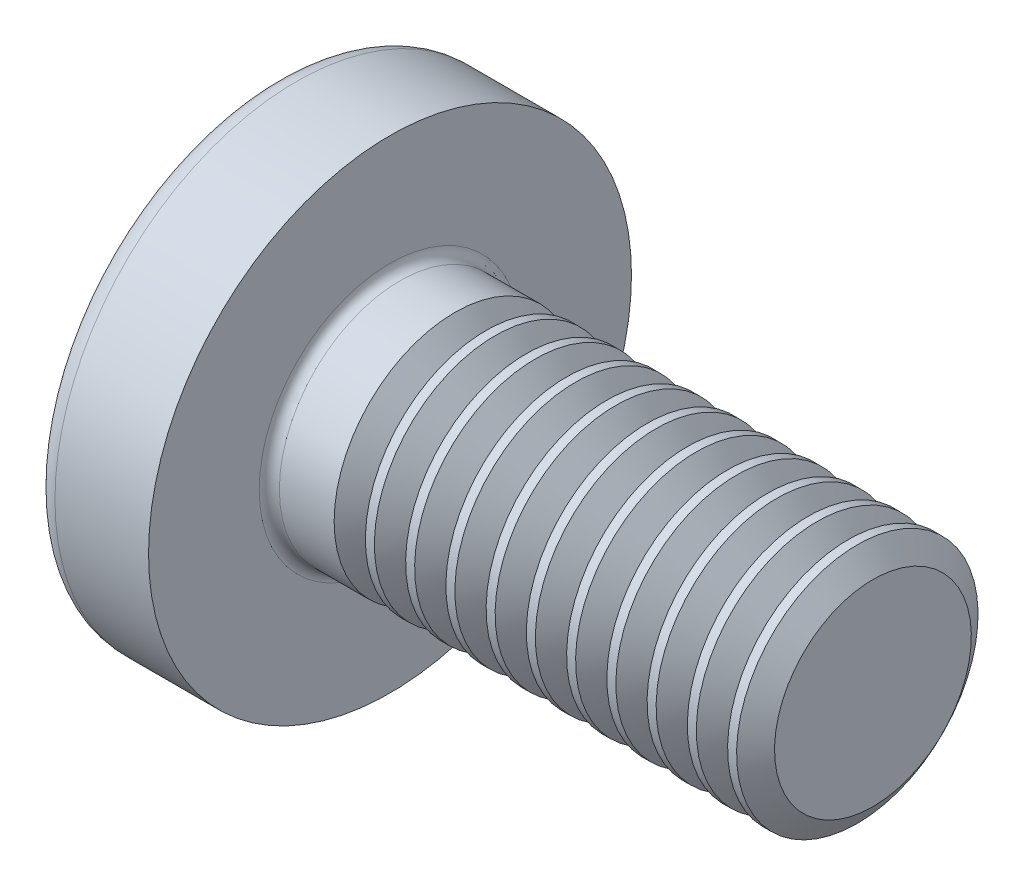
SolidWorks part; units mm, degrees
ref_plane "Plane1" through (0, 0, 0) normal (0, 0, 1) x (1, 0, 0)
ref_plane "Plane2" through (0, 0, 0) normal (0, 1, 0) x (1, 0, 0)
ref_plane "Plane3" through (0, 0, 0) normal (1, 0, 0) x (0, 0, -1)
sketch "BodySke" plane through (0, 0, 0) normal (0, 0, 1) x (1, 0, 0)
  line L0 (4.6, 3) -> (4.6, 6)
  line L1 (5.1, 6.35) -> (5.1, -3.175) construction
  line L2 (-25.4, 0) -> (127, 0) construction
  line L3 (16.6, 0) -> (0, 0)
  line L4 (4.6, 3) -> (16.6, 3)
  line L5 (16.6, 3) -> (16.6, 0)
  line L6 (2.2747, 6) -> (4.6, 6)
  line L8 (4.6, 6.35) -> (4.6, -3.175) construction
  arc A0 (1.8337, 5.7717) -> (0, 0) centre (10, 0) ccw
  arc A2 (1.8337, 5.7717) -> (2.2747, 6) centre (2.2747, 5.46) cw
  dimension "Head_fillet_rad" = 0.54
  dimension "Head_crown_rad" = 10
  dimension "Head_ht" = 4.6
  dimension "Diameter" = 6
  dimension "Length" = 12
  dimension "Head_dia" = 12
  dimension "Advance" = 1
  dimension "Thread_nom" = 12
revolve "Base-Revolve" add sketch "BodySke"
cosmetic thread "ThreadCosmetic" [suppressed]
fillet "Fillet1" radius 0.25 1 edges at (4.6, 0, 3)
sketch "Sketch3" plane through (0, 0, 0) normal (1, 0, 0) x (0, 0, -1)
  line L0 (0.71, -3.35) -> (-0.71, -3.35)
  line L1 (0.71, -3.35) -> (0.71, 3.35)
  line L2 (-0.71, 3.35) -> (0.71, 3.35)
  line L3 (-0.71, 3.35) -> (-0.71, -3.35)
  dimension "D1" = 3.35
  dimension "Cross_dia" = 6.7
  dimension "D2" = 0.71
  dimension "Cross_width" = 1.42
ref_plane "Plane4" through (3.46, 0, 0) normal (1, 0, 0) x (0, 0, -1)
sketch "Sketch4" plane through (3.46, 0, 0) normal (1, 0, 0) x (0, 0, -1)
  line L0 (0.71, -1.6249) -> (-0.71, -1.6249)
  line L1 (0.71, -1.6249) -> (0.71, 1.6249)
  line L2 (-0.71, 1.6249) -> (0.71, 1.6249)
  line L3 (-0.71, 1.6249) -> (-0.71, -1.6249)
  dimension "D1" = 1.42
  dimension "D2" = 3.2498
  dimension "D3" = 0.71
  dimension "D4" = 1.6249
loft "Recess" cut profiles "Sketch3", "Sketch4"
pattern_circular "RecPat" count 2 every 90 about axis through (0, 0, 0) along (1, 0, 0) of "Recess"
sketch "RecCorSke" plane through (0, 0, 0) normal (0, 0, 1) x (1, 0, 0)
  line L0 (-3.175, 0) -> (15.875, 0) construction
  line L1 (-25.4, 0) -> (127, 0) construction
  line L2 (0, 0) -> (0, 1.5224)
  line L3 (0, 1.5224) -> (3.46, 1.2805)
  line L4 (3.46, 1.2805) -> (3.8761, 0)
  line L5 (3.8761, 0) -> (0, 0)
  dimension "Diameter" = 2.561
  dimension "Depth" = 3.46
  dimension "Draft_angle" = 4
  dimension "Bottom_angle" = 18
revolve "RecessCore" cut sketch "RecCorSke" angle 360 about L0
sketch "ThdSchSke" plane through (0, 0, 0) normal (0, 0, 1) x (1, 0, 0)
  line L0 (6.6, -2.4455) -> (6.2117, -3)
  line L1 (6.6, -2.4455) -> (6.9883, -3)
  line L2 (6.9883, -3) -> (6.9883, -3.75)
  line L3 (-3.175, 0) -> (5.1513, 0) construction
  line L5 (6.9883, -3.75) -> (6.2117, -3.75)
  line L6 (6.2117, -3.75) -> (6.2117, -3)
  dimension "Thread_minor" = 4.891
  dimension "Diameter" = 6
  dimension "Start" = 6.6
  dimension "SideAngle" = 55
  dimension "VeeAngle" = 70
  dimension "Overcut" = 7.5
revolve "ThreadSchematic" cut sketch "ThdSchSke" angle 360 about L3
pattern_linear "ThdSchPat" count 11 spacing 1 along (1, 0, 0) of "ThreadSchematic"
equation "\"D1@Sketch3\" = \"Cross_dia@Sketch3\" / 2"
equation "\"D2@Sketch3\" = \"Cross_width@Sketch3\" / 2"
equation "\"Depth@RecCorSke\" = \"Cross_depth@Plane4\""
equation "\"D1@Sketch4\" = \"Cross_width@Sketch3\""
equation "\"D2@Sketch4\" = \"Cross_dia@Sketch3\" - 2.0 * \"Cross_depth@Plane4\" * tan(26.5  * 0.017453292)"
equation "\"D3@Sketch4\" = \"D1@Sketch4\" / 2"
equation "\"D4@Sketch4\" = \"D2@Sketch4\" / 2"
equation "\"Thread_length@ThreadCosmetic\" = ((sgn( (\"Length@BodySke\" - \"Advance@BodySke\" * 2.0 ) - \"Thread_nom@BodySke\" )-1)*( (\"Length@BodySke\" - \"Advance@BodySke\" * 2.0 ) - \"Thread_nom@BodySke\" ))/-2+ \"Thread_nom@BodySke\""
equation "\"Thread_minor@ThdSchSke\" = \"Thread_minor@ThreadCosmetic\""
equation "\"Diameter@ThdSchSke\" = \"Diameter@BodySke\""
equation "\"Overcut@ThdSchSke\" = \"Diameter@BodySke\" * 1.25"
equation "\"Start@ThdSchSke\" = \"Head_ht@BodySke\" + \"Length@BodySke\" - \"Thread_length@ThreadCosmetic\"  '---Non-countersunk---"
equation "\"Num_threads@ThdSchPat\" = int( \"Thread_length@ThreadCosmetic\" / \"Advance@BodySke\" + 0.999 )  + 1"
equation "\"Advance@ThdSchPat\" = \"Thread_length@ThreadCosmetic\" /  (\"Num_threads@ThdSchPat\" - 1) 'relax it"
